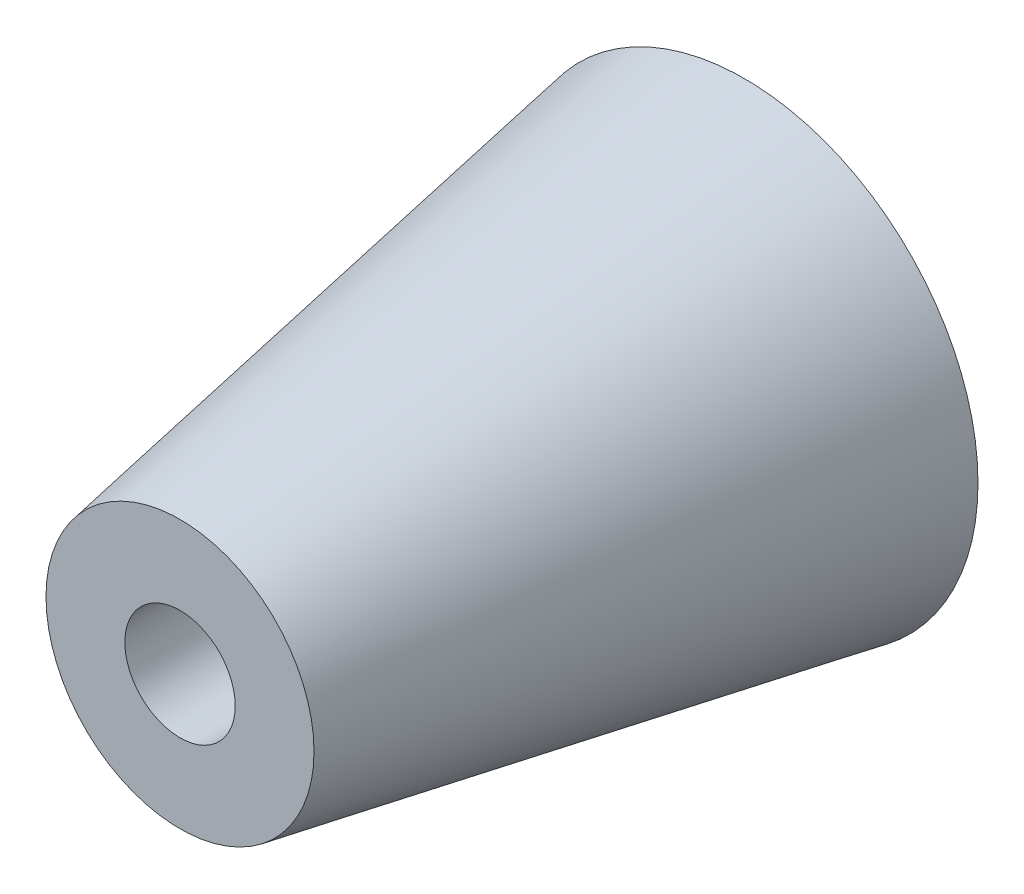
SolidWorks part; units mm, degrees
material "ABS"
ref_plane "Front Plane" through (0, 0, 0) normal (0, 0, 1) x (1, 0, 0)
ref_plane "Top Plane" through (0, 0, 0) normal (0, 1, 0) x (1, 0, 0)
ref_plane "Right Plane" through (0, 0, 0) normal (1, 0, 0) x (0, 0, -1)
sketch "Sketch1" plane through (0, 0, 0) normal (1, 0, 0) x (0, 0, -1)
  line L0 (-51.4955, 0) -> (51.4955, 0) construction
  line L1 (-33.7154, 3.5) -> (-28.7154, 3.5)
  line L2 (-33.7154, 8.5) -> (2.0846, 14.8125)
  line L5 (-33.7154, 8.5) -> (-33.7154, 3.5)
  line L8 (2.0846, 9.463) -> (2.0846, 14.8125)
  line L11 (-28.7154, 3.5) -> (2.0846, 9.463)
  dimension "D2" = 5
  dimension "D5" = 5
  dimension "D7" = 3.5
revolve "Revolve1" add sketch "Sketch1" angle 360 about L0
